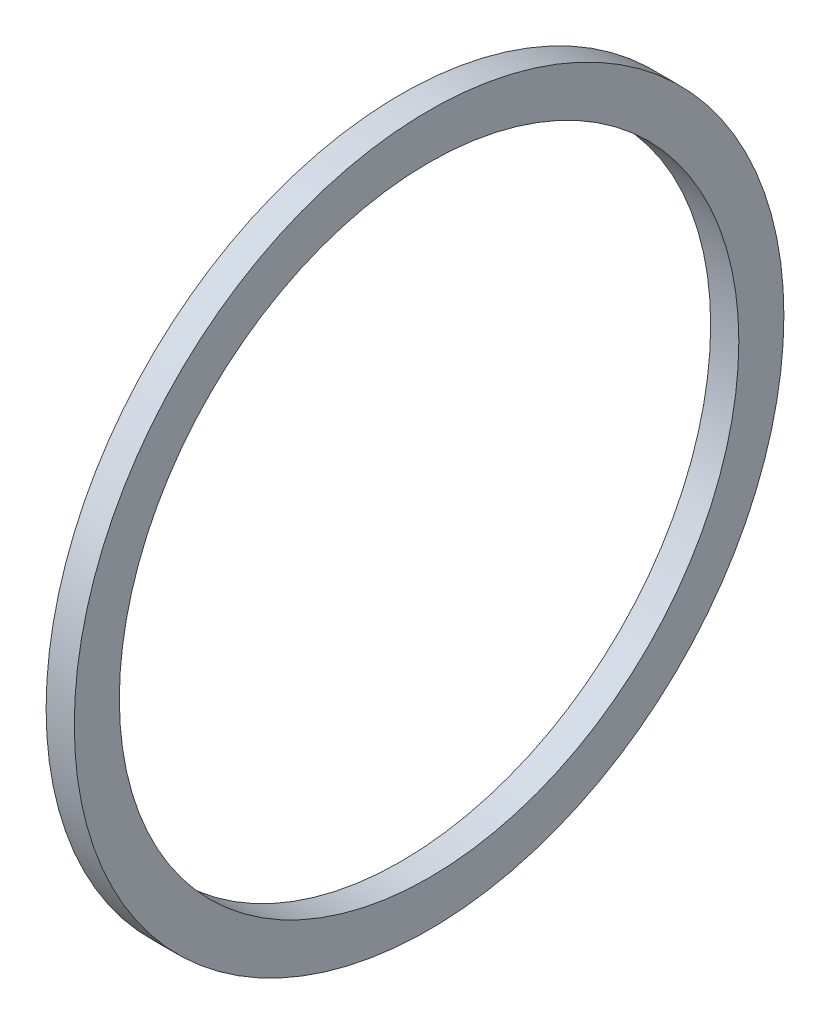
SolidWorks part; units mm, degrees
ref_plane "Front Plane" through (0, 0, 0) normal (0, 0, 1) x (1, 0, 0)
ref_plane "Top Plane" through (0, 0, 0) normal (0, 1, 0) x (1, 0, 0)
ref_plane "Right Plane" through (0, 0, 0) normal (1, 0, 0) x (0, 0, -1)
sketch "Sketch1" plane through (0, 0, 0) normal (1, 0, 0) x (0, 0, -1)
  circle A0 centre (0, 0) radius 18.9
  circle A1 centre (0, 0) radius 16.5
  dimension "D1" = 37.8
  dimension "D2" = 33
extrude "Boss-Extrude1" add sketch "Sketch1" along normal blind 1.5
